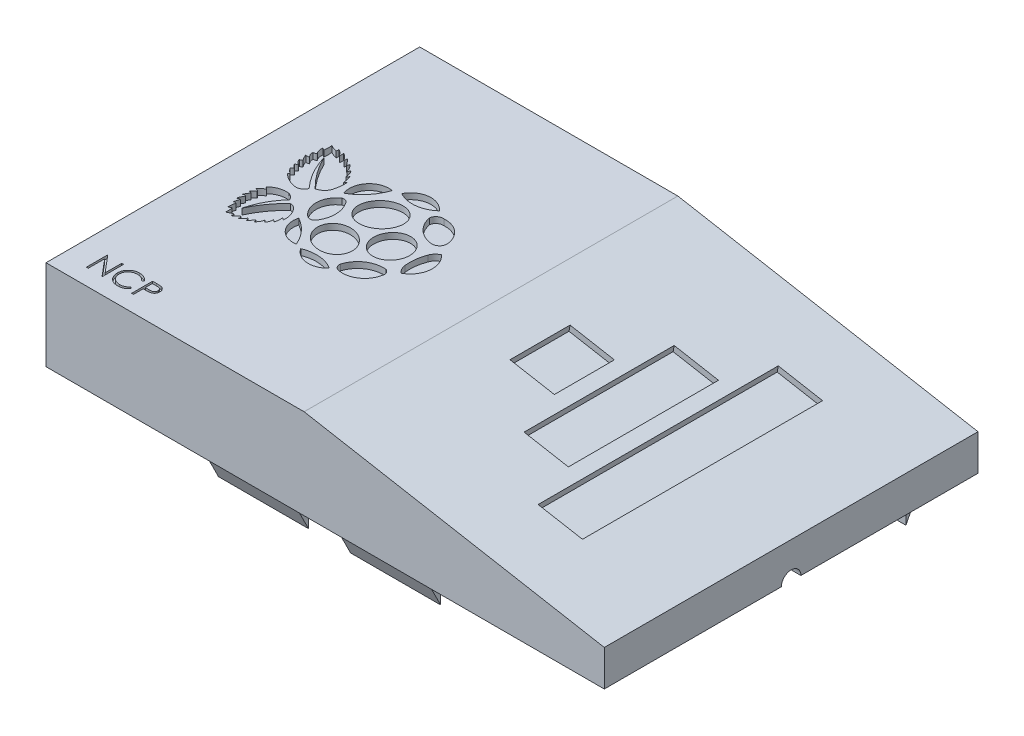
SolidWorks part; units mm, degrees
ref_plane "Front Plane" through (0, 0, 0) normal (0, 0, 1) x (1, 0, 0)
ref_plane "Top Plane" through (0, 0, 0) normal (0, 1, 0) x (1, 0, 0)
ref_plane "Right Plane" through (0, 0, 0) normal (1, 0, 0) x (0, 0, -1)
sketch "Sketch1" plane through (0, 0, 0) normal (0, 0, 1) x (1, 0, 0)
  line L0 (93, 6) -> (43, 15)
  line L1 (0, 0) -> (93, 0)
  line L2 (0, 0) -> (0, 15)
  line L3 (0, 15) -> (93, 15)
  line L4 (93, 0) -> (93, 15)
  dimension "D1" = 93
  dimension "D2" = 15
  dimension "D3" = 50
  dimension "D4" = 6
extrude "Boss-Extrude1" add sketch "Sketch1" along normal blind 62.25 contours L1 L4 L0 L3 L2
sketch "Sketch4" plane through (93, 0, 0) normal (1, 0, 0) x (0, 0, -1)
  line L0 (-62.25, 0) -> (0, 0) construction
  line L1 (-32.75, 0) -> (-29.5, 0)
  arc A0 (-32.75, 0) -> (-29.5, 0) centre (-31.125, 0) cw
  dimension "D1" = 3.25
shell "Shell2" thickness 3
sketch "Sketch2" plane through (0, 15, 0) normal (0, 1, 0) x (1, 0, 0)
  line L0 (-235, 102.2083) -> (-235, 742.2083) construction
  arc A0 (19.1857, -38.996) -> (24.3948, -39.4285) centre (21.3683, -44.2937) cw
  arc A1 (24.3948, -39.4285) -> (19.1857, -38.996) centre (21.954, -37.2406) cw
  arc A2 (18.1666, -38.72) -> (14.6196, -34.759) centre (17.6584, -35.6065) cw
  arc A3 (24.7168, -37.8763) -> (25.47, -38.9985) centre (25.6468, -38.066) ccw
  arc A4 (25.47, -38.9985) -> (29.8405, -36.0322) centre (26.1668, -35.3224) ccw
  arc A5 (29.8405, -36.0322) -> (29.2441, -34.88) centre (28.9662, -35.7543) ccw
  arc A6 (29.2441, -34.88) -> (24.7168, -37.8763) centre (28.8501, -39.2031) ccw
  arc A7 (31.0992, -34.1702) -> (31.7849, -28.1665) centre (29.4013, -30.9353) ccw
  arc A8 (31.0992, -34.1702) -> (30.2857, -32.7229) centre (32.4066, -32.4831) cw
  arc A9 (31.7849, -28.1665) -> (30.7169, -29.2978) centre (32.6009, -30.0067) ccw
  arc A10 (30.2857, -32.7229) -> (30.7169, -29.2978) centre (37.5652, -31.8997) cw
  arc A11 (18.1666, -38.72) -> (14.6196, -34.759) centre (10.6651, -41.8687) ccw
  arc A12 (15.3082, -33.8951) -> (15.3082, -28.2916) centre (17.2139, -31.0934) cw
  arc A13 (15.3082, -33.8951) -> (16.4919, -33.4059) centre (15.6554, -33.0587) ccw
  arc A14 (16.4919, -33.4059) -> (16.4156, -28.7835) centre (12.7201, -31.1563) ccw
  arc A15 (16.4156, -28.7835) -> (15.3082, -28.2916) centre (15.616, -29.0913) ccw
  arc A16 (19.6587, -22.6474) -> (25.2838, -22.0075) centre (22.0296, -18.4441) ccw
  arc A17 (25.2838, -22.0075) -> (19.6587, -22.6474) centre (22.6811, -24.1718) ccw
  arc A18 (30.7169, -26.154) -> (26.8142, -22.7745) centre (27.0758, -26.4156) ccw
  arc A19 (26.8142, -22.7745) -> (25.47, -23.8439) centre (26.6768, -23.9813) ccw
  arc A20 (25.47, -23.8439) -> (29.4013, -27.4175) centre (29.8242, -23.0031) ccw
  arc A21 (29.4013, -27.4175) -> (30.7169, -26.154) centre (29.4274, -26.128) ccw
  arc A22 (14.7675, -27.4175) -> (18.4191, -23.0031) centre (10.9853, -20.5713) ccw
  arc A23 (18.4191, -23.0031) -> (14.7675, -27.4175) centre (17.8352, -26.2376) ccw
  arc A24 (11.7511, -29.1754) -> (7.9856, -23.9279) centre (24.5394, -16.0237) cw
  arc A25 (7.9856, -23.9279) -> (11.219, -29.6376) centre (21.5886, -19.9947) ccw
  arc A26 (11.7511, -29.1754) -> (13.3658, -27.4175) centre (11.3134, -27.1529) ccw
  arc A27 (13.3658, -27.4175) -> (13.5282, -25.574) centre (7.0254, -25.9298) ccw
  arc A28 (13.2053, -25.8811) -> (13.5282, -25.574) centre (12.5521, -24.871) ccw
  arc A29 (13.2053, -25.8811) -> (12.9017, -24.4996) centre (7.3236, -26.4498) ccw
  arc A30 (12.9017, -24.4996) -> (12.5808, -24.8404) centre (12.2904, -24.2456) cw
  arc A31 (12.5808, -24.8404) -> (12.1321, -23.5773) centre (10.6591, -24.8119) ccw
  arc A32 (12.1321, -23.5773) -> (11.9013, -23.9813) centre (11.4778, -23.4714) cw
  arc A33 (11.9013, -23.9813) -> (11.1571, -22.7745) centre (9.5633, -24.5903) ccw
  arc A34 (11.1571, -22.7745) -> (10.9853, -23.1885) centre (9.405, -22.2902) cw
  arc A35 (10.9853, -23.1885) -> (10.1111, -22.1783) centre (7.3184, -25.4784) ccw
  arc A36 (10.1111, -22.1783) -> (10.0041, -22.6495) centre (9.1577, -22.2095) cw
  arc A37 (10.0041, -22.6495) -> (8.9761, -21.6415) centre (7.9611, -23.7049) ccw
  arc A38 (8.9761, -21.6415) -> (8.9761, -22.363) centre (8.1491, -22.0023) cw
  arc A39 (8.9761, -22.363) -> (8.0542, -21.5057) centre (6.9698, -23.5961) ccw
  arc A40 (8.0542, -21.5057) -> (8.0354, -21.9508) centre (7.3765, -21.6999) cw
  arc A41 (8.0354, -21.9508) -> (6.9023, -21.5194) centre (8.5799, -18.817) cw
  arc A42 (6.9023, -21.5194) -> (6.9023, -22.8672) centre (0.5963, -22.1933) cw
  arc A43 (6.9023, -22.8672) -> (6.5382, -22.6314) centre (7.5936, -21.4006) cw
  arc A44 (6.5382, -22.6314) -> (6.8251, -23.873) centre (7.9728, -22.9539) ccw
  arc A45 (6.8251, -23.873) -> (6.3242, -24.0709) centre (6.4427, -23.6381) cw
  arc A46 (6.3242, -24.0709) -> (6.6854, -25.0284) centre (7.5452, -24.1572) ccw
  arc A47 (6.6854, -25.0284) -> (6.1117, -25.0437) centre (6.3874, -24.6219) cw
  arc A48 (6.1117, -25.0437) -> (6.6076, -26.0197) centre (8.209, -24.5919) ccw
  arc A49 (6.6076, -26.0197) -> (6.2106, -26.2117) centre (6.3131, -25.9171) cw
  arc A50 (6.2106, -26.2117) -> (6.7731, -26.9726) centre (7.1266, -26.1229) ccw
  arc A51 (6.7731, -26.9726) -> (6.4268, -27.2683) centre (6.4521, -26.9473) cw
  arc A52 (6.4268, -27.2683) -> (7.0254, -27.9176) centre (7.9408, -26.4731) ccw
  arc A53 (7.0254, -27.9176) -> (6.6447, -28.2241) centre (6.5115, -27.669) cw
  arc A54 (7.4633, -29.0592) -> (6.6447, -28.2241) centre (9.2589, -26.4804) cw
  arc A55 (7.4633, -29.0592) -> (7.2327, -29.2482) centre (7.1822, -28.9514) cw
  arc A56 (7.2327, -29.2482) -> (10.0041, -30.5481) centre (10.3254, -26.2589) ccw
  arc A57 (10.0041, -30.5481) -> (11.219, -29.6376) centre (9.8338, -29.0552) ccw
  arc A58 (13.6054, -36.3181) -> (12.9978, -34.0614) centre (10.1665, -36.0339) ccw
  arc A59 (12.9978, -34.0614) -> (11.8058, -33.3593) centre (11.7714, -34.7806) ccw
  arc A60 (8.4367, -38.0756) -> (11.8058, -33.3593) centre (22.1613, -44.3183) cw
  arc A61 (8.4367, -38.0756) -> (11.2035, -32.882) centre (20.0622, -40.9351) cw
  arc A62 (11.2035, -32.882) -> (10.2337, -32.0031) centre (9.7284, -33.5351) ccw
  arc A63 (10.2337, -32.0031) -> (7.361, -33.0201) centre (9.7569, -35.222) ccw
  arc A64 (7.361, -33.0201) -> (7.7525, -33.264) centre (7.2472, -33.6388) cw
  arc A65 (6.7576, -34.0709) -> (7.7525, -33.264) centre (9.1956, -36.0603) cw
  arc A66 (6.7576, -34.0709) -> (7.2774, -34.3391) centre (6.7661, -34.6923) cw
  arc A67 (7.2774, -34.3391) -> (6.5921, -34.985) centre (8.626, -36.4564) ccw
  arc A68 (6.5921, -34.985) -> (7.051, -35.1215) centre (6.6412, -35.6597) cw
  arc A69 (7.051, -35.1215) -> (6.496, -35.9948) centre (8.8929, -36.9051) ccw
  arc A70 (7.0099, -36.0105) -> (6.496, -35.9948) centre (6.7429, -36.332) ccw
  arc A71 (6.5227, -37.0957) -> (7.0099, -36.0105) centre (9.8529, -37.939) cw
  arc A72 (6.5227, -37.0957) -> (7.0638, -36.9387) centre (7.0093, -37.7623) cw
  arc A73 (7.0638, -36.9387) -> (6.834, -37.9046) centre (9.1706, -37.9502) ccw
  arc A74 (6.834, -37.9046) -> (7.2472, -37.8533) centre (7.0663, -38.0855) cw
  arc A75 (7.2472, -37.8533) -> (7.1111, -39.1079) centre (9.7277, -38.757) ccw
  arc A76 (7.1111, -39.1079) -> (7.5296, -38.7855) centre (8.8071, -40.8767) cw
  arc A77 (7.5296, -38.7855) -> (7.619, -40.0185) centre (5.5682, -39.5474) cw
  arc A78 (7.619, -40.0185) -> (8.6416, -39.5474) centre (10.1779, -44.2273) cw
  arc A79 (8.6416, -39.5474) -> (8.5942, -40.0185) centre (7.493, -39.6698) cw
  arc A80 (8.5942, -40.0185) -> (9.4452, -39.2791) centre (8.1382, -38.6343) ccw
  arc A81 (9.6166, -39.8143) -> (9.4452, -39.2791) centre (9.2633, -39.6324) ccw
  arc A82 (9.6166, -39.8143) -> (10.3861, -38.996) centre (8.7675, -38.2449) ccw
  arc A83 (10.5573, -39.4673) -> (10.3861, -38.996) centre (9.871, -39.4498) ccw
  arc A84 (10.5573, -39.4673) -> (11.3134, -38.5743) centre (7.2397, -35.8912) ccw
  arc A85 (11.4483, -38.996) -> (11.3134, -38.5743) centre (10.8284, -38.9619) ccw
  arc A86 (11.4483, -38.996) -> (12.0743, -37.8437) centre (10.1462, -37.5425) ccw
  arc A87 (12.0743, -37.8437) -> (12.2904, -38.2442) centre (11.765, -38.2692) cw
  arc A88 (12.2904, -38.2442) -> (12.7201, -37.1052) centre (11.3263, -37.2299) ccw
  arc A89 (12.7201, -37.1052) -> (13.0788, -37.3998) centre (12.5344, -37.6969) cw
  arc A90 (13.0788, -37.3998) -> (13.2053, -36.0507) centre (10.8098, -36.5064) ccw
  arc A91 (13.2053, -36.0507) -> (13.6054, -36.3181) centre (12.6047, -37.3825) cw
  ellipse E0 centre (20.6313, -34.759) end of major axis (23.6045, -36.0321) minor radius 2.8362
  ellipse E1 centre (26.4308, -31.0934) end of major axis (27.5777, -28.2916) minor radius 2.7936
  ellipse E2 centre (20.9728, -27.4175) end of major axis (23.6712, -25.2814) minor radius 2.8794
extrude "Cut-Extrude1" cut sketch "Sketch2" against normal blind 1
sketch "Sketch3" plane through (0, 15, 0) normal (0, 1, 0) x (1, 0, 0)
  text T0 "NCP"
extrude "Cut-Extrude2" cut sketch "Sketch3" against normal blind 0.5
extrude "Cut-Extrude3" cut sketch "Sketch4" against normal blind 3
sketch "Sketch5" plane through (3.9647, 22.0263, 0) normal (0.1772, 0.9842, 0) x (0.9842, -0.1772, 0)
  line L0 (90.4661, -62.25) -> (90.4661, 0) construction
  line L1 (67.9661, -51.125) -> (75.4661, -51.125)
  line L2 (67.9661, -51.125) -> (67.9661, -11.125)
  line L3 (67.9661, -11.125) -> (75.4661, -11.125)
  line L4 (75.4661, -51.125) -> (75.4661, -11.125)
  line L5 (57.9661, -43.625) -> (65.4661, -43.625)
  line L6 (57.9661, -43.625) -> (57.9661, -18.625)
  line L7 (57.9661, -18.625) -> (65.4661, -18.625)
  line L8 (65.4661, -43.625) -> (65.4661, -18.625)
  line L9 (47.9661, -36.125) -> (55.4661, -36.125)
  line L10 (47.9661, -36.125) -> (47.9661, -26.125)
  line L11 (47.9661, -26.125) -> (55.4661, -26.125)
  line L12 (55.4661, -36.125) -> (55.4661, -26.125)
  point P12 (75.4661, -31.125)
  point P15 (90.4661, -31.125)
  point P16 (65.4661, -31.125)
  point P17 (55.4661, -31.125)
  dimension "D1" = 40
  dimension "D2" = 25
  dimension "D3" = 10
  dimension "D4" = 7.5
  dimension "D5" = 7.5
  dimension "D6" = 7.5
  dimension "D7" = 2.5
  dimension "D8" = 2.5
  dimension "D9" = 15
extrude "Cut-Extrude4" cut sketch "Sketch5" against normal blind 1
sketch "Sketch6" plane through (0, 12, 0) normal (0, -1, 0) x (1, 0, 0)
  line L0 (3, 3) -> (42.7322, 3) construction
  line L1 (3, 59.25) -> (3, 3) construction
  circle A0 centre (34.75, 10.75) radius 1.75
  circle A1 centre (8.25, 29.25) radius 1.75
  dimension "D3" = 3.5
  dimension "D1" = 7.75
  dimension "D2" = 31.75
  dimension "D4" = 5.25
  dimension "D5" = 26.25
extrude "Boss-Extrude2" add sketch "Sketch6" along normal offset from surface (10.25 mm away) 1.75 up to face at (61.5, 0, 31.125)
sketch "Sketch7" plane through (0, 1.75, 0) normal (0, -1, 0) x (1, 0, 0)
  circle A0 centre (8.25, 29.25) radius 0.775
  circle A1 centre (34.75, 10.75) radius 0.775
  dimension "D1" = 1.55
extrude "Boss-Extrude3" add sketch "Sketch7" along normal blind 5.75
sketch "Sketch8" plane through (0, 0, 0) normal (0, -1, 0) x (1, 0, 0)
  line L0 (3, 3) -> (90, 3) construction
  line L1 (72, 3) -> (87, 3)
  line L2 (72, 3) -> (72, 6)
  line L3 (72, 6) -> (87, 6)
  line L4 (87, 3) -> (87, 6)
  line L6 (3, 59.25) -> (90, 59.25) construction
  line L7 (44.7322, 59.25) -> (59.7322, 59.25)
  line L8 (44.7322, 59.25) -> (44.7322, 56.25)
  line L9 (44.7322, 56.25) -> (59.7322, 56.25)
  line L10 (59.7322, 59.25) -> (59.7322, 56.25)
  line L13 (42.7322, 59.25) -> (42.7322, 3) construction
  line L15 (90, 29.5) -> (90, 3) construction
  dimension "D1" = 15
  dimension "D2" = 2
  dimension "D3" = 3
  dimension "D4" = 3
extrude "Boss-Extrude4" add sketch "Sketch8" against normal up to surface (6.7318 mm away)
sketch "Sketch9" plane through (0, 0, 0) normal (0, -1, 0) x (1, 0, 0)
  line L0 (3, 59.25) -> (44.7322, 59.25) construction
  line L1 (37.7322, 59.25) -> (22.7322, 59.25)
  line L2 (37.7322, 59.25) -> (37.7322, 56.25)
  line L3 (37.7322, 56.25) -> (22.7322, 56.25)
  line L4 (22.7322, 59.25) -> (22.7322, 56.25)
  line L5 (42.7322, 59.25) -> (42.7322, 3) construction
  dimension "D1" = 5
  dimension "D2" = 15
  dimension "D3" = 3
extrude "Boss-Extrude5" add sketch "Sketch9" against normal up to next
sketch "Sketch10" plane through (0, 0, 0) normal (0, -1, 0) x (-1, 0, 0)
  line L0 (-72, -6) -> (-72, -3) construction
  line L1 (-87, -6) -> (-72, -6)
  line L2 (-87, -6) -> (-87, -5)
  line L3 (-87, -5) -> (-72, -5)
  line L4 (-72, -6) -> (-72, -5)
  line L5 (-59.7322, -56.25) -> (-59.7322, -59.25) construction
  line L6 (-44.7322, -56.25) -> (-59.7322, -56.25)
  line L7 (-44.7322, -56.25) -> (-44.7322, -57.25)
  line L8 (-44.7322, -57.25) -> (-59.7322, -57.25)
  line L9 (-59.7322, -56.25) -> (-59.7322, -57.25)
  line L10 (-37.7322, -56.25) -> (-37.7322, -59.25) construction
  line L11 (-22.7322, -56.25) -> (-37.7322, -56.25)
  line L12 (-22.7322, -56.25) -> (-22.7322, -57.25)
  line L13 (-22.7322, -57.25) -> (-37.7322, -57.25)
  line L14 (-37.7322, -56.25) -> (-37.7322, -57.25)
  line L16 (-87, -3) -> (-87, -6) construction
  line L17 (-87, -6) -> (-72, -6) construction
  point P21 (0, 0)
  dimension "D1" = 1
extrude "Boss-Extrude6" add sketch "Sketch10" along normal blind 5.5
sketch "Sketch12" plane through (37.7322, 0, 0) normal (1, 0, 0) x (0, 0, -1)
  line L0 (-57.25, -5.5) -> (-57.75, -4.5)
  line L1 (-57.75, -4.5) -> (-57.25, -4.5)
  line L2 (-57.25, -5.5) -> (-57.25, 0) construction
  line L3 (-57.25, -4.5) -> (-57.25, -5.5) construction
  line L4 (-57.25, -4.5) -> (-56.25, -4.5)
  line L5 (-56.25, 12) -> (-56.25, -5.5) construction
  line L6 (-56.25, -4.5) -> (-56.25, -7.5)
  line L7 (-56.25, -7.5) -> (-57.25, -5.5)
  dimension "D1" = 1
  dimension "D2" = 0.5
extrude "Boss-Extrude8" add sketch "Sketch12" against normal up to surface (15 mm away) up to face at (22.7322, 2.1667, 57.5833)
sketch "Sketch14" plane through (0, 12, 0) normal (0, -1, 0) x (1, 0, 0)
  line L1 (5.75, 26.75) -> (10.75, 26.75)
  line L2 (5.75, 26.75) -> (5.75, 31.75)
  line L3 (5.75, 31.75) -> (10.75, 31.75)
  line L4 (10.75, 26.75) -> (10.75, 31.75)
  line L5 (32.25, 8.25) -> (37.25, 8.25)
  line L6 (32.25, 8.25) -> (32.25, 13.25)
  line L7 (32.25, 13.25) -> (37.25, 13.25)
  line L8 (37.25, 8.25) -> (37.25, 13.25)
  circle A0 centre (8.25, 29.25) radius 2.5 construction
  circle A1 centre (34.75, 10.75) radius 2.5 construction
  dimension "D1" = 5
extrude "Boss-Extrude9" add sketch "Sketch14" along normal offset from surface (8.25 mm away) 2 up to face at (8.25, 1.75, 28.475)
sketch "Sketch15" plane through (87, 0, 0) normal (1, 0, 0) x (0, 0, -1)
  line L0 (-5, -4.5) -> (-4.5, -4.5)
  line L1 (-5, -5.5) -> (-5, 0) construction
  line L2 (-4.5, -4.5) -> (-6, -7.5)
  line L3 (-6, -7.5) -> (-6, -4.5)
  line L4 (-6, -5.5) -> (-6, 4.0318) construction
  line L5 (-5, -4.5) -> (-6, -4.5)
  dimension "D1" = 0.5
  dimension "D2" = 1
extrude "Boss-Extrude10" add sketch "Sketch15" against normal up to surface (15 mm away) up to face at (72, 0.4106, 4.6667)
sketch "Sketch16" plane through (59.7322, 0, 0) normal (1, 0, 0) x (0, 0, -1)
  line L0 (-56.25, -4.5) -> (-56.25, -7.5)
  line L1 (-56.25, 8.94) -> (-56.25, -5.5) construction
  line L2 (-56.25, -7.5) -> (-57.75, -4.5)
  line L3 (-57.75, -4.5) -> (-56.25, -4.5)
  line L4 (-57.25, -4.5) -> (-57.75, -4.5) construction
  line L5 (-57.75, -4.5) -> (-56.25, -7.5) construction
extrude "Boss-Extrude11" add sketch "Sketch16" against normal up to surface (15 mm away) up to face at (44.7322, 2.0467, 57.5833)
